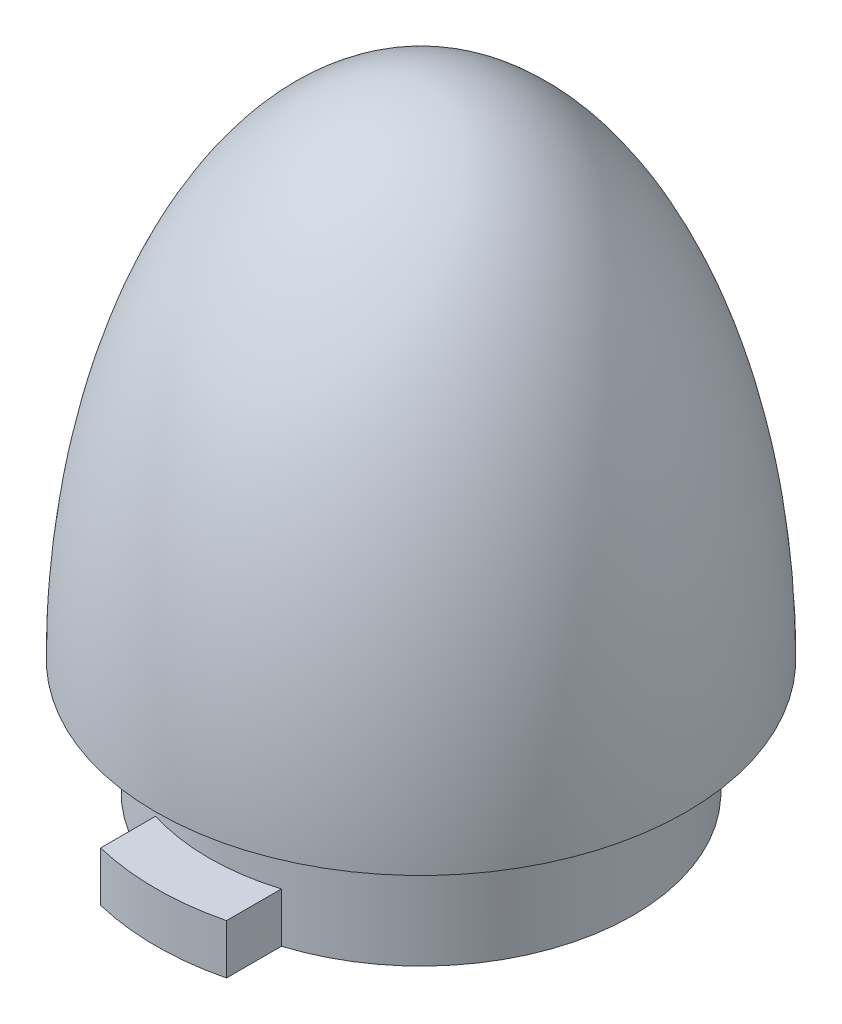
SolidWorks part; units mm, degrees
ref_plane "Front Plane" through (0, 0, 0) normal (0, 0, 1) x (1, 0, 0)
ref_plane "Top Plane" through (0, 0, 0) normal (0, 1, 0) x (1, 0, 0)
ref_plane "Right Plane" through (0, 0, 0) normal (1, 0, 0) x (0, 0, -1)
sketch "Sketch1" plane through (0, 0, 0) normal (1, 0, 0) x (0, 0, -1)
  line L0 (-8.128, 0) -> (-8.128, 4.445)
  line L1 (55, 0) -> (-55, 0) construction
  line L2 (-8.128, 4.445) -> (-10.16, 4.445)
  line L3 (0, 55) -> (0, -55) construction
  line L4 (-6.096, 6.477) -> (-8.0665, 6.477)
  line L5 (-6.096, 0) -> (-6.096, 6.477)
  line L6 (-8.128, 0) -> (-6.096, 0)
  line L7 (0, 21.463) -> (0, 23.495)
  line L8 (0, 0) -> (0, 23.495) construction
  ellipse E0 centre (0, 4.445) end of major axis (0, -14.605) minor radius 10.16 (0, 23.495) -> (-10.16, 4.445) ccw
  spline S0 degree 1 poles (0, 21.463) (-8.0665, 6.477) knots 0 0 1 1 construction
  spline S1 degree 3 poles (0, 21.463) (-0.3983, 21.463) (-1.1534, 21.3358) (-2.4294, 20.6847) (-3.76, 19.4747) (-5.0456, 17.6992) (-6.1855, 15.4167) (-7.1085, 12.7129) (-7.7633, 9.7078) (-8.0016, 7.5452) (-8.0665, 6.477) knots 3.141593 3.141593 3.141593 3.141593 3.32377 3.505948 3.688126 3.870303 4.052481 4.234659 4.416836 4.599014 4.599014 4.599014 4.599014
  dimension "D1" = 8.128
  dimension "D2" = 2.032
  dimension "D3" = 19.05
  dimension "D4" = 4.445
  dimension "D5" = 2.032
revolve "Revolve1" add sketch "Sketch1" angle 360 about L8
sketch "Sketch2" plane through (0, 4.445, 0) normal (0, -1, 0) x (1, 0, 0)
  line L0 (-2.413, 9.8693) -> (-2.413, 7.7616)
  line L1 (0, -55) -> (0, 55) construction
  line L3 (2.413, 9.8693) -> (2.413, 7.7616)
  line L4 (55, 0) -> (-55, 0) construction
  line L5 (2.413, -9.8693) -> (2.413, -7.7616)
  line L6 (-2.413, -9.8693) -> (-2.413, -7.7616)
  circle A0 centre (0, 0) radius 10.16 construction
  circle A1 centre (0, 0) radius 8.128 construction
  arc A2 (-2.413, -7.7616) -> (2.413, -7.7616) centre (0, 0) ccw
  arc A3 (-2.413, -9.8693) -> (2.413, -9.8693) centre (0, 0) ccw
  arc A4 (2.413, 7.7616) -> (-2.413, 7.7616) centre (0, 0) ccw
  arc A5 (2.413, 9.8693) -> (-2.413, 9.8693) centre (0, 0) ccw
  dimension "D1" = 4.826
extrude "Boss-Extrude1" add sketch "Sketch2" against normal blind 1.905 from surface at 4.445 starting at face at (0, 0, -6.096)
